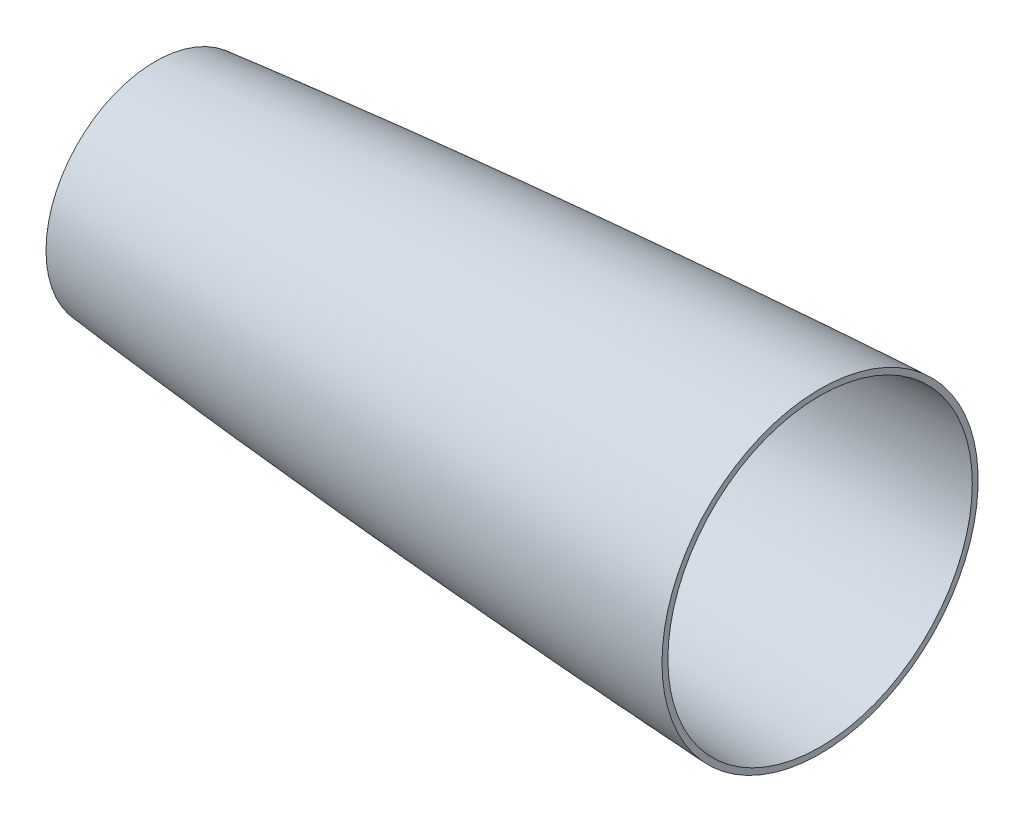
SolidWorks part; units mm, degrees
ref_plane "Front Plane" through (0, 0, 0) normal (0, 0, 1) x (1, 0, 0)
ref_plane "Top Plane" through (0, 0, 0) normal (0, 1, 0) x (1, 0, 0)
ref_plane "Right Plane" through (0, 0, 0) normal (1, 0, 0) x (0, 0, -1)
sketch "Sketch1" plane through (0, 0, 0) normal (0, 1, 0) x (1, 0, 0)
  line L2 (186.2, 30.5942) -> (186.2, 0)
  line L3 (186.2, 0) -> (372.4, 0)
  line L4 (372.4, 0) -> (372.4, 44.2733)
  spline S0 degree 4 poles (167.7526, 28.6744) (168.0659, 28.7079) (168.6708, 28.7727) (169.6836, 28.882) (171.7184, 29.0969) (173.2895, 29.2653) (176.8672, 29.6377) (179.17, 29.88) (184.53, 30.4259) (186.785, 30.6538) (191.9188, 31.1664) (196.1244, 31.5784) (201.8409, 32.1311) (207.8937, 32.7017) (214.2054, 33.2858) (220.3684, 33.8426) (226.6222, 34.3966) (232.8228, 34.9334) (239.0572, 35.462) (245.2727, 35.9774) (251.501, 36.4828) (259.1272, 37.088) (268.3177, 37.7966) (279.059, 38.5948) (289.8135, 39.3588) (299.1501, 39.9971) (306.9504, 40.5135) (313.1597, 40.9153) (319.4324, 41.3106) (325.595, 41.6909) (331.9449, 42.0709) (337.9854, 42.4262) (344.538, 42.7977) (350.248, 43.1179) (357.3494, 43.4983) (362.1482, 43.755) (370.2189, 44.165) (373.3789, 44.3228) (379.8398, 44.6389) (383.2011, 44.7975) (387.1054, 44.9813) (389.1954, 45.0766) (390.4621, 45.1349) (391.0241, 45.1604) knots 0 0 0 0 0 0.005205 0.01041 0.02082 0.031231 0.041641 0.062209 0.082777 0.096722 0.110666 0.138556 0.166445 0.194334 0.222224 0.250113 0.278003 0.305892 0.333782 0.361671 0.38956 0.41745 0.470511 0.52629 0.582069 0.609958 0.637848 0.665737 0.693627 0.721516 0.749405 0.777295 0.805184 0.833074 0.860963 0.888853 0.916742 0.937557 0.958371 0.979186 0.989593 1 1 1 1 1 construction
  spline S1 degree 4 poles (186.2, 30.5942) (186.8477, 30.6594) (188.1681, 30.7919) (191.9188, 31.1664) (196.1244, 31.5784) (201.8409, 32.1311) (207.8937, 32.7017) (214.2054, 33.2858) (220.3684, 33.8426) (226.6222, 34.3966) (232.8228, 34.9334) (239.0572, 35.462) (245.2727, 35.9774) (251.501, 36.4828) (259.1272, 37.088) (268.3177, 37.7966) (279.059, 38.5948) (289.8135, 39.3588) (299.1501, 39.9971) (306.9504, 40.5135) (313.1597, 40.9153) (319.4324, 41.3106) (325.595, 41.6909) (331.9449, 42.0709) (337.9854, 42.4262) (344.538, 42.7977) (350.248, 43.1179) (357.3494, 43.4983) (362.1482, 43.755) (368.6111, 44.0833) (371.0997, 44.2086) (372.4, 44.2733) knots 0.082777 0.082777 0.082777 0.082777 0.082777 0.096722 0.110666 0.138556 0.166445 0.194334 0.222224 0.250113 0.278003 0.305892 0.333782 0.361671 0.38956 0.41745 0.470511 0.52629 0.582069 0.609958 0.637848 0.665737 0.693627 0.721516 0.749405 0.777295 0.805184 0.833074 0.860963 0.888853 0.916742 0.916742 0.916742 0.916742 0.916742
revolve "Revolve2" add sketch "Sketch1" angle 360 about L3
shell "Shell3" thickness 1.64
sketch "Sketch2" plane through (187.84, 0, 0) normal (1, 0, 0) x (0, 0, -1)
  circle A0 centre (0, 0) radius 29.1106
extrude "Cut-Extrude1" cut sketch "Sketch2" against normal blind 10
